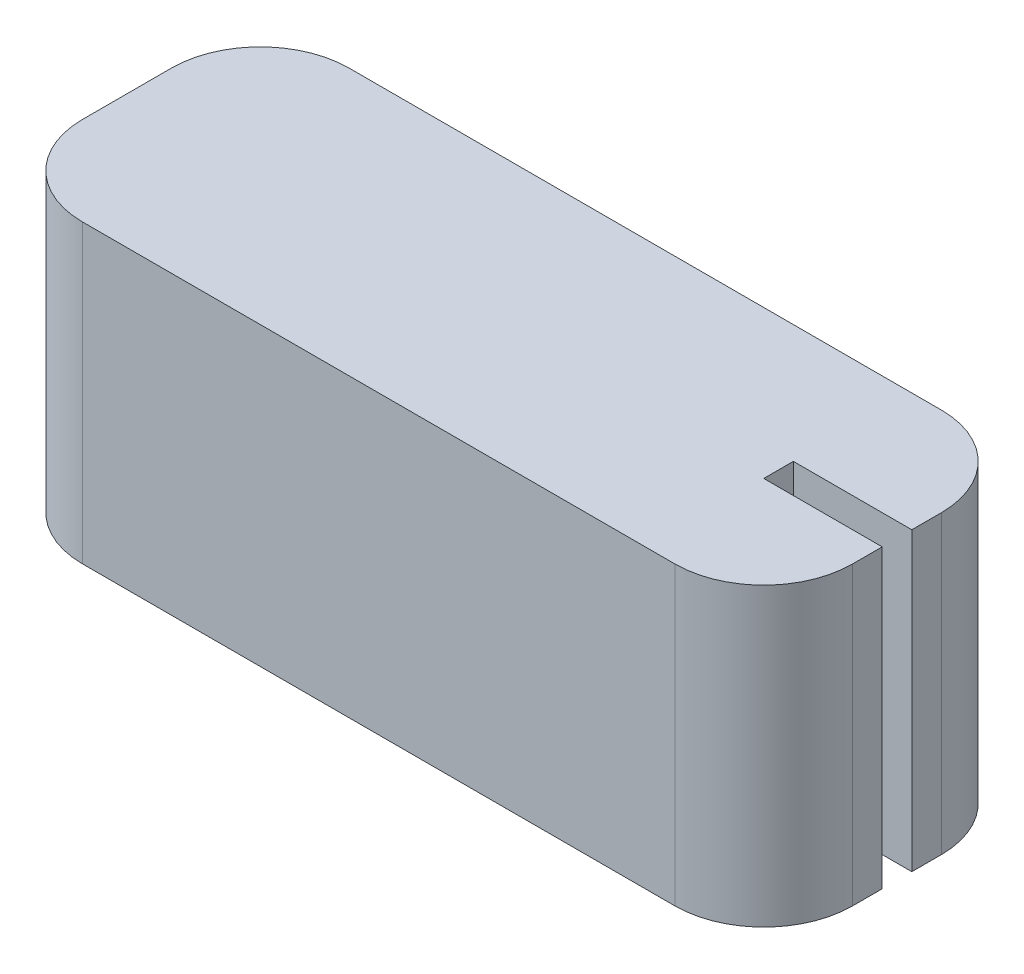
SolidWorks part; units mm, degrees
ref_plane "Front Plane" through (0, 0, 0) normal (0, 0, 1) x (1, 0, 0)
ref_plane "Top Plane" through (0, 0, 0) normal (0, 1, 0) x (1, 0, 0)
ref_plane "Right Plane" through (0, 0, 0) normal (1, 0, 0) x (0, 0, -1)
sketch "Sketch1" plane through (0, 0, 0) normal (0, 1, 0) x (1, 0, 0)
  circle A0 centre (0, 0) radius 3.65
  dimension "D1" = 7.3
extrude "Boss-Extrude1" add sketch "Sketch1" along normal blind 5
sketch "Sketch3" plane through (0, 5, 0) normal (0, 1, 0) x (1, 0, 0)
  line L0 (0.2457, -3.6417) -> (15.775, -2.5941)
  line L1 (15.775, 2.5941) -> (0.2457, 3.6417)
  arc A0 (15.775, -2.5941) -> (15.775, 2.5941) centre (15.6, 0) ccw
  circle A1 centre (0, 0) radius 3.65 construction
  arc A2 (0.2457, -3.6417) -> (0.2457, 3.6417) centre (0, 0) ccw
  dimension "D1" = 15.6
  dimension "D2" = 2.6
extrude "Boss-Extrude2" add sketch "Sketch3" against normal blind 1
sketch "Sketch4" plane through (0, 5, 0) normal (0, 1, 0) x (1, 0, 0)
  line L1 (-5, 4.5) -> (21, 4.5)
  line L2 (0.2457, -3.6417) -> (15.775, -2.5941)
  line L3 (15.775, 2.5941) -> (0.2457, 3.6417)
  line L4 (0.2457, -3.6417) -> (15.775, -2.5941)
  line L5 (15.775, 2.5941) -> (0.2457, 3.6417)
  line L6 (-5, 4.5) -> (-5, -4.5)
  line L7 (-5, -4.5) -> (21, -4.5)
  line L8 (21, 4.5) -> (21, -4.5)
  arc A2 (0.2457, 3.6417) -> (0.2457, -3.6417) centre (0, 0) ccw
  arc A3 (15.775, -2.5941) -> (15.775, 2.5941) centre (15.6, 0) ccw
  arc A4 (0.2457, 3.6417) -> (0.2457, -3.6417) centre (0, 0) ccw
  arc A5 (15.775, -2.5941) -> (15.775, 2.5941) centre (15.6, 0) ccw
  dimension "D4" = 5.4
  dimension "D2" = 4.5
  dimension "D3" = 26
  dimension "D5" = 4.5
  dimension "D1" = 0
extrude "Boss-Extrude3" add sketch "Sketch4" against normal blind 5 separate body
sketch "Sketch5" plane through (0, 5, 0) normal (0, 1, 0) x (1, 0, 0)
  line L1 (-5, 4.5) -> (21, 4.5)
  line L2 (-5, 4.5) -> (-5, -4.5)
  line L3 (-5, -4.5) -> (21, -4.5)
  line L4 (21, 4.5) -> (21, -4.5)
extrude "Boss-Extrude4" add sketch "Sketch5" along normal blind 5
ref_plane "Plane1" through (8, 0, 0) normal (-1, 0, 0) x (0, 0, 1)
sketch "Sketch6" plane through (21, 0, 0) normal (1, 0, 0) x (0, 0, -1)
  line L0 (0, 10) -> (0, 0)
  line L1 (-4.5, 10) -> (4.5, 10) construction
extrude "Cut-Extrude-Thin1" cut sketch "Sketch6" against normal blind 4 thin thin type mid plane wall 1
fillet "Fillet1" radius 3 2 edges at (-5, 5, -4.5) (-5, 5, 4.5)
fillet "Fillet2" radius 3 2 edges at (21, 5, -4.5) (21, 5, 4.5)
